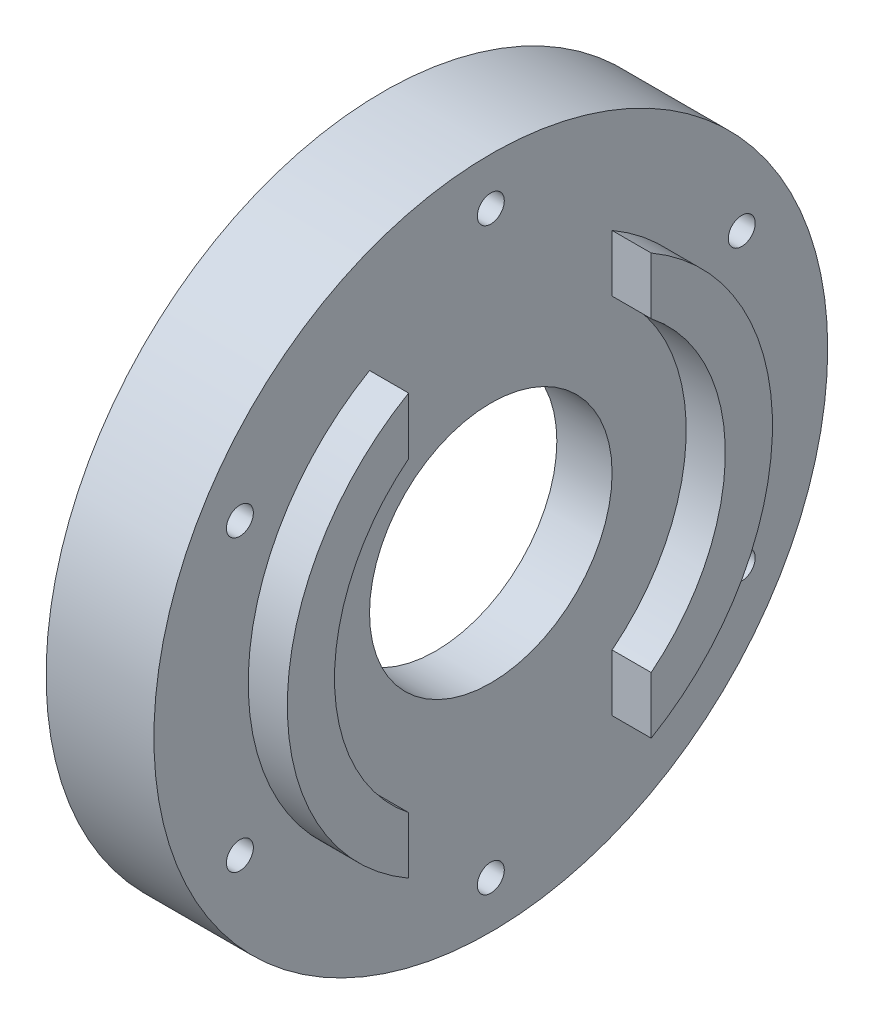
SolidWorks part; units mm, degrees
ref_plane "Front Plane" through (0, 0, 0) normal (0, 0, 1) x (1, 0, 0)
ref_plane "Top Plane" through (0, 0, 0) normal (0, 1, 0) x (1, 0, 0)
ref_plane "Right Plane" through (0, 0, 0) normal (1, 0, 0) x (0, 0, -1)
sketch "Sketch1" plane through (0, 0, 0) normal (1, 0, 0) x (0, 0, -1)
  line L0 (0, 0) -> (0, 125) construction
  line L1 (0, 0) -> (-125, 0) construction
  line L2 (-62.5, 108.2532) -> (0, 0) construction
  line L3 (0, 0) -> (62.5, 108.2532) construction
  circle A0 centre (0, 0) radius 125
  circle A1 centre (0, 0) radius 45
  circle A2 centre (0, 0) radius 107.5 construction
  circle A3 centre (0, 107.5) radius 5
  circle A4 centre (93.0977, 53.75) radius 5
  circle A5 centre (-93.0977, 53.75) radius 5
  circle A6 centre (-93.0977, -53.75) radius 5
  circle A7 centre (0, -107.5) radius 5
  circle A8 centre (93.0977, -53.75) radius 5
  dimension "D1" = 90
  dimension "D2" = 250
  dimension "D5" = 215
  dimension "D6" = 10
  dimension "D3" = 30
  dimension "D4" = 30
extrude "Boss-Extrude1" add sketch "Sketch1" against normal blind 40
sketch "Sketch2" plane through (0, 0, 0) normal (1, 0, 0) x (0, 0, -1)
  circle A0 centre (0, 0) radius 41.51
  circle A1 centre (0, 0) radius 45
  circle A2 centre (0, 0) radius 45 construction
  dimension "D1" = 83.02
sketch "Sketch3" plane through (0, 0, 0) normal (1, 0, 0) x (0, 0, -1)
  circle A0 centre (0, 0) radius 90
  circle A1 centre (0, 0) radius 72.5
  dimension "D1" = 180
  dimension "D2" = 145
extrude "Boss-Extrude2" add sketch "Sketch3" along normal blind 14.5
sketch "Sketch4" plane through (0, 0, 0) normal (0, 1, 0) x (1, 0, 0)
  line L0 (0, -90) -> (0, 90) construction
  line L1 (0, 45) -> (14.5, 45)
  line L2 (0, 45) -> (0, -45)
  line L3 (0, -45) -> (14.5, -45)
  line L4 (14.5, 45) -> (14.5, -45)
  line L5 (14.5, -90) -> (14.5, 90) construction
  point P8 (0, 0)
  dimension "D1" = 90
extrude "Cut-Extrude1" cut sketch "Sketch4" against normal through all both and the other way through all
ref_plane "Plane1" through (-40, 0, 0) normal (-1, 0, 0) x (0, 0, 1)
sketch "Sketch5" plane through (-40, 0, 0) normal (-1, 0, 0) x (0, 0, 1)
  circle A0 centre (0, 0) radius 100
  dimension "D1" = 200
extrude "Cut-Extrude3" cut sketch "Sketch5" against normal blind 19.5
ref_plane "Plane2" through (-20.5, 0, 0) normal (-1, 0, 0) x (0, 0, 1)
sketch "Sketch6" plane through (-20.5, 0, 0) normal (-1, 0, 0) x (0, 0, 1)
  line L0 (0, 0) -> (0, 45) construction
  line L1 (0, 0) -> (108.2532, 62.5) construction
  line L2 (0, 0) -> (-108.2532, 62.5) construction
  line L3 (0, 0) -> (45, 0) construction
  line L4 (0, 0) -> (77.9423, -45) construction
  line L5 (-77.9423, -45) -> (0, 0) construction
  circle A0 centre (0, 0) radius 90
  circle A1 centre (0, 0) radius 45 construction
  circle A2 centre (0, 0) radius 125 construction
  point P0 (77.9423, 45)
  point P1 (0, 90)
  point P18 (-77.9423, 45)
  point P20 (77.9423, -45)
  point P21 (-77.9423, -45)
  point P22 (0, -90)
  dimension "D1" = 180
  dimension "D2" = 60
  dimension "D3" = 60
hole_wizard "Ø8.0mm Dowel Hole1" positions "Sketch7" profile "Sketch8" hole size "Ø8.0" standard "ISO"
sketch "Sketch7" plane through (-20.5, 0, 0) normal (-1, 0, 0) x (0, 0, 1)
  point P0 (0, 90)
  point P3 (77.9423, 45)
  point P9 (77.9423, -45)
  point P12 (0, -90)
  point P15 (-77.9423, -45)
  point P21 (-77.9423, 45)
sketch "Sketch8" plane through (-20.5, 90, 0) normal (0, 1, 0) x (0, 0, 1)
  line L0 (0, 0) -> (0, 12.4034)
  line L1 (0, 12.4034) -> (4, 10)
  line L2 (4, 10) -> (4, 0)
  line L5 (4, 0) -> (0, 0)
  line L10 (0, 12.4034) -> (-4, 10) construction
  line L11 (0, -6.35) -> (0, 107.95) construction
  dimension "Hole Dia." = 8
  dimension "Hole Depth" = 10
  dimension "Drill Angle" = 118
